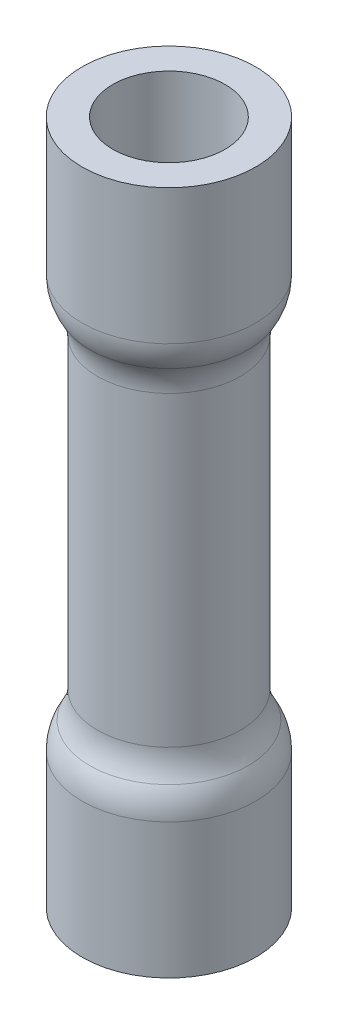
SolidWorks part; units mm, degrees
material "PVC 0.007 Plasticized"
ref_plane "Front Plane" through (0, 0, 0) normal (0, 0, 1) x (1, 0, 0)
ref_plane "Top Plane" through (0, 0, 0) normal (0, 1, 0) x (1, 0, 0)
ref_plane "Right Plane" through (0, 0, 0) normal (1, 0, 0) x (0, 0, -1)
sketch "Sketch1" plane through (0, 0, 0) normal (0, 0, 1) x (1, 0, 0)
  line L0 (1.778, 12.319) -> (1.778, 4.699)
  line L1 (2.159, 0) -> (2.159, 3.361)
  line L2 (0, 8.509) -> (2.159, 8.509) construction
  line L3 (2.159, 13.657) -> (2.159, 17.018)
  line L5 (0, 17.018) -> (0, 0) construction
  arc A0 (2.159, 3.361) -> (1.9685, 4.03) centre (0.889, 3.361) ccw
  arc A1 (1.9685, 4.03) -> (1.778, 4.699) centre (3.048, 4.699) cw
  arc A2 (2.159, 13.657) -> (1.9685, 12.988) centre (0.889, 13.657) cw
  arc A3 (1.9685, 12.988) -> (1.778, 12.319) centre (3.048, 12.319) ccw
  point P8 (0, 0)
  point P19 (0, 0)
  dimension "D5" = 1.27
  dimension "D1" = 17.018
  dimension "D2" = 2.159
  dimension "D3" = 0.381
  dimension "D4" = 7.62
revolve "Revolve-Thin1" add sketch "Sketch1" angle 360 about L5
